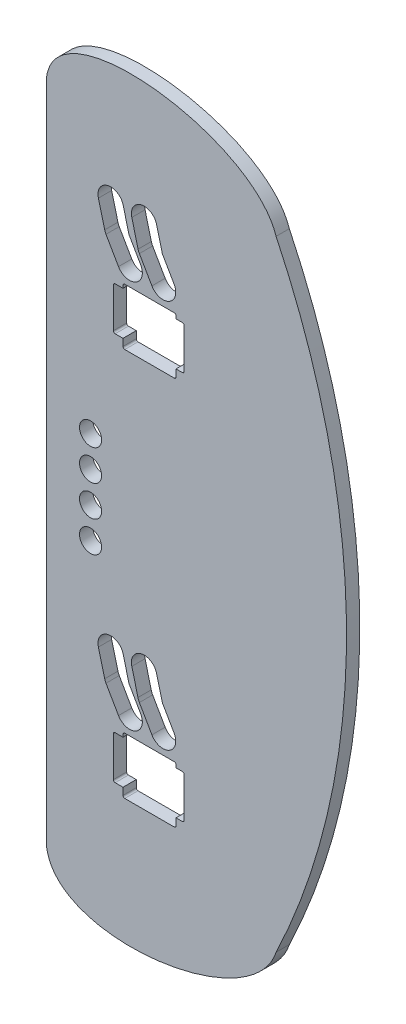
SolidWorks part; units mm, degrees
material "Pine"
ref_plane "Front Plane" through (0, 0, 0) normal (0, 0, 1) x (1, 0, 0)
ref_plane "Top Plane" through (0, 0, 0) normal (0, 1, 0) x (1, 0, 0)
ref_plane "Right Plane" through (0, 0, 0) normal (1, 0, 0) x (0, 0, -1)
sketch "Sketch1" plane through (0, 0, 0) normal (0, 1, 0) x (1, 0, 0)
  line L0 (-92.9216, 89.0184) -> (669.0784, 89.0184)
  line L1 (669.0784, 89.0184) -> (669.0784, 419.2184)
  line L2 (-92.9216, 89.0184) -> (-92.9216, 419.2184)
  line L5 (110.2784, 495.4184) -> (465.8784, 495.4184)
  line L8 (110.2784, 495.4184) -> (-92.9216, 419.2184)
  line L9 (465.8784, 495.4184) -> (669.0784, 419.2184)
  line L10 (-92.9216, 495.4184) -> (669.0784, 495.4184) construction
sketch "Sketch2" plane through (0, 0, 0) normal (0, 0, 1) x (1, 0, 0)
  line L95 (1361.0966, 1819.7347) -> (1361.0966, 996.3635)
  arc A0 (1691.2966, 1027.0491) -> (1691.2966, 1789.0491) centre (733.0004, 1408.0491) ccw
  spline S0 degree 3 poles (1691.2966, 1027.0491) (1656.7077, 922.0591) (1371.3251, 886.2968) (1361.0966, 996.3635) knots 0 0 0 0 7.629784 7.629784 7.629784 7.629784
  spline S1 degree 3 poles (1691.2966, 1789.0491) (1656.7629, 1894.0573) (1371.3251, 1929.8013) (1361.0966, 1819.7347) knots 0 0 0 0 7.638295 7.638295 7.638295 7.638295
sketch "Sketch5" plane through (0, 0, 0) normal (0, 0, 1) x (1, 0, 0)
  line L0 (1361.0966, 1819.7347) -> (1361.0966, 996.3635)
  line L1 (1361.0966, 1789.0491) -> (1361.0966, 1027.0491)
  line L2 (1540.0357, 1006.8697) -> (1540.0357, 1016.3947)
  line L3 (1486.0607, 1097.3572) -> (1486.0607, 1006.8697) construction
  line L4 (1486.0607, 1102.1197) -> (1486.0607, 1092.5947)
  line L5 (1540.0357, 1006.8697) -> (1540.0357, 1097.3572) construction
  line L6 (1544.7982, 1102.1197) -> (1481.2982, 1102.1197) construction
  line L7 (1486.0607, 1006.8697) -> (1540.0357, 1006.8697)
  line L8 (1479.7107, 1016.3947) -> (1546.3857, 1016.3947)
  line L9 (1546.3857, 1016.3947) -> (1546.3857, 1092.5947)
  line L10 (1546.3857, 1092.5947) -> (1479.7107, 1092.5947)
  line L11 (1479.7107, 1016.3947) -> (1479.7107, 1092.5947)
  line L12 (1540.0357, 1548.8399) -> (1540.0357, 1558.3649)
  line L13 (1486.0607, 1548.8399) -> (1540.0357, 1548.8399)
  line L14 (1546.3857, 1634.5649) -> (1479.7107, 1634.5649)
  line L15 (1486.0607, 1644.0899) -> (1486.0607, 1634.5649)
  line L16 (1479.7107, 1558.3649) -> (1479.7107, 1634.5649)
  line L17 (1540.0357, 1644.0899) -> (1486.0607, 1644.0899)
  line L18 (1479.7107, 1558.3649) -> (1546.3857, 1558.3649)
  line L19 (1546.3857, 1558.3649) -> (1546.3857, 1634.5649)
  line L20 (1540.0357, 1092.5947) -> (1540.0357, 1102.1197)
  line L21 (1486.0607, 1016.3947) -> (1486.0607, 1006.8697)
  line L22 (1540.0357, 1634.5649) -> (1540.0357, 1644.0899)
  line L23 (1486.0607, 1558.3649) -> (1486.0607, 1548.8399)
  line L95 (1361.0966, 1819.7347) -> (1361.0966, 996.3635)
  line L115 (1540.0357, 1102.1197) -> (1486.0607, 1102.1197)
  line L199 (1363.2449, 1823.8418) -> (1361.0966, 1819.7347)
  line L200 (1361.0966, 1819.7347) -> (1361.7967, 1824.3165)
  line L201 (1361.7967, 1824.3165) -> (1363.2449, 1823.8418)
  line L202 (1540.0357, 1097.3572) -> (1486.0607, 1097.3572) construction
  line L203 (1481.2982, 1102.1197) -> (1481.2982, 1006.8697) construction
  line L204 (1544.7982, 1006.8697) -> (1544.7982, 1102.1197) construction
  arc A0 (1691.2966, 1027.0491) -> (1691.2966, 1789.0491) centre (733.0004, 1408.0491) ccw
  circle A1 centre (1506.0488, 1194.0197) radius 15.875
  circle A2 centre (1515.0488, 1159.0198) radius 15.875
  circle A3 centre (1533.0488, 1127.7698) radius 15.875
  circle A4 centre (1467.0488, 1159.0198) radius 15.875
  circle A5 centre (1485.0488, 1127.7698) radius 15.875
  circle A6 centre (1458.0488, 1194.0197) radius 15.875
  circle A7 centre (1513.0482, 1054.4947) radius 12
  circle A8 centre (1506.0488, 1735.9899) radius 15.875
  circle A9 centre (1515.0488, 1700.99) radius 15.875
  circle A10 centre (1533.0488, 1669.74) radius 15.875
  circle A11 centre (1467.0488, 1700.99) radius 15.875
  circle A12 centre (1485.0488, 1669.74) radius 15.875
  circle A13 centre (1458.0488, 1735.9899) radius 15.875
  circle A15 centre (1483.5084, 1375.1967) radius 12
  circle A16 centre (1483.9827, 1438.6917) radius 12
  circle A17 centre (1551.8392, 1408.0266) radius 29.9999
  circle A18 centre (1409.3368, 1408.0266) radius 15.9995
  circle A19 centre (1513.0482, 1596.4649) radius 12
  arc A30 (1539.4945, 1725.9331) -> (1482.0488, 1761.3623) centre (1506.0488, 1735.9899) ccw
  arc A32 (1549.9668, 1700.2938) -> (1539.4945, 1725.9331) centre (1515.0488, 1700.99) ccw
  arc A41 (1509.0488, 1644.3676) -> (1549.9668, 1700.2938) centre (1533.0488, 1669.74) ccw
  arc A46 (1450.1308, 1670.4362) -> (1509.0488, 1644.3676) centre (1485.0488, 1669.74) ccw
  arc A47 (1433.6031, 1711.0467) -> (1450.1308, 1670.4362) centre (1467.0488, 1700.99) ccw
  arc A50 (1482.0488, 1761.3623) -> (1433.6031, 1711.0467) centre (1458.0488, 1735.9899) ccw
  arc A64 (1509.0488, 1102.3974) -> (1549.9668, 1158.3235) centre (1533.0488, 1127.7698) ccw
  arc A66 (1450.1308, 1128.466) -> (1509.0488, 1102.3974) centre (1485.0488, 1127.7698) ccw
  arc A68 (1433.6031, 1169.0765) -> (1450.1308, 1128.466) centre (1467.0488, 1159.0198) ccw
  arc A70 (1539.4945, 1183.9629) -> (1482.0488, 1219.3921) centre (1506.0488, 1194.0197) ccw
  arc A72 (1549.9668, 1158.3235) -> (1539.4945, 1183.9629) centre (1515.0488, 1159.0198) ccw
  arc A73 (1482.0488, 1219.3921) -> (1433.6031, 1169.0765) centre (1458.0488, 1194.0197) ccw
  arc A86 (1474.249, 1382.8299) -> (1489.0021, 1364.5282) centre (1483.5084, 1375.1967) ccw
  arc A89 (1488.8753, 1449.649) -> (1474.6166, 1431.19) centre (1483.9827, 1438.6917) ccw
  arc A97 (1557.861, 1378.6372) -> (1557.0728, 1437.5665) centre (1551.8392, 1408.0266) ccw
  arc A99 (1420.1657, 1419.8299) -> (1400.5179, 1421.402) centre (1409.3362, 1408.0491) ccw
  arc A100 (1402.6554, 1393.5084) -> (1419.641, 1395.8067) centre (1409.3362, 1408.0491) ccw
  spline S0 degree 3 poles (1691.2966, 1027.0491) (1656.7077, 922.0591) (1371.3251, 886.2968) (1361.0966, 996.3635) knots 0 0 0 0 7.629784 7.629784 7.629784 7.629784
  spline S1 degree 3 poles (1691.2966, 1789.0491) (1656.7629, 1894.0573) (1371.3251, 1929.8013) (1361.0966, 1819.7347) knots 0 0 0 0 7.638295 7.638295 7.638295 7.638295
  dimension "D1" = 4.7625
sketch "Sketch8" plane through (0, 0, 0) normal (0, 0, 1) x (1, 0, 0)
  line L2 (1540.0357, 1006.8697) -> (1540.0357, 1016.3947)
  line L3 (1486.0607, 1097.3572) -> (1486.0607, 1006.8697) construction
  line L4 (1486.0607, 1102.1197) -> (1486.0607, 1092.5947)
  line L5 (1540.0357, 1006.8697) -> (1540.0357, 1097.3572) construction
  line L6 (1544.7982, 1102.1197) -> (1481.2982, 1102.1197) construction
  line L7 (1486.0607, 1006.8697) -> (1540.0357, 1006.8697)
  line L8 (1479.7107, 1016.3947) -> (1546.3857, 1016.3947)
  line L9 (1546.3857, 1016.3947) -> (1546.3857, 1092.5947)
  line L10 (1546.3857, 1092.5947) -> (1479.7107, 1092.5947)
  line L11 (1479.7107, 1016.3947) -> (1479.7107, 1092.5947)
  line L12 (1540.0357, 1548.8399) -> (1540.0357, 1558.3649)
  line L13 (1486.0607, 1548.8399) -> (1540.0357, 1548.8399)
  line L14 (1546.3857, 1634.5649) -> (1479.7107, 1634.5649)
  line L15 (1486.0607, 1644.0899) -> (1486.0607, 1634.5649)
  line L16 (1479.7107, 1558.3649) -> (1479.7107, 1634.5649)
  line L17 (1540.0357, 1644.0899) -> (1486.0607, 1644.0899)
  line L18 (1479.7107, 1558.3649) -> (1546.3857, 1558.3649)
  line L19 (1546.3857, 1558.3649) -> (1546.3857, 1634.5649)
  line L20 (1540.0357, 1092.5947) -> (1540.0357, 1102.1197)
  line L21 (1486.0607, 1016.3947) -> (1486.0607, 1006.8697)
  line L22 (1540.0357, 1634.5649) -> (1540.0357, 1644.0899)
  line L23 (1486.0607, 1558.3649) -> (1486.0607, 1548.8399)
  line L95 (1361.0966, 1819.7347) -> (1361.0966, 996.3635)
  line L115 (1540.0357, 1102.1197) -> (1486.0607, 1102.1197)
  line L202 (1540.0357, 1097.3572) -> (1486.0607, 1097.3572) construction
  line L203 (1481.2982, 1102.1197) -> (1481.2982, 1006.8697) construction
  line L204 (1544.7982, 1006.8697) -> (1544.7982, 1102.1197) construction
  arc A0 (1691.2966, 1027.0491) -> (1691.2966, 1789.0491) centre (733.0004, 1408.0491) ccw
  circle A1 centre (1506.0488, 1194.0197) radius 15.875
  circle A2 centre (1515.0488, 1159.0198) radius 15.875
  circle A3 centre (1533.0488, 1127.7698) radius 15.875
  circle A4 centre (1467.0488, 1159.0198) radius 15.875
  circle A5 centre (1485.0488, 1127.7698) radius 15.875
  circle A6 centre (1458.0488, 1194.0197) radius 15.875
  circle A7 centre (1513.0482, 1054.4947) radius 12
  circle A8 centre (1506.0488, 1735.9899) radius 15.875
  circle A9 centre (1515.0488, 1700.99) radius 15.875
  circle A10 centre (1533.0488, 1669.74) radius 15.875
  circle A11 centre (1467.0488, 1700.99) radius 15.875
  circle A12 centre (1485.0488, 1669.74) radius 15.875
  circle A13 centre (1458.0488, 1735.9899) radius 15.875
  circle A15 centre (1483.5084, 1375.1967) radius 12
  circle A16 centre (1483.9827, 1438.6917) radius 12
  circle A17 centre (1551.8392, 1408.0266) radius 29.9999
  circle A18 centre (1409.3368, 1408.0266) radius 15.9995
  circle A19 centre (1513.0482, 1596.4649) radius 12
  arc A30 (1539.4945, 1725.9331) -> (1482.0488, 1761.3623) centre (1506.0488, 1735.9899) ccw
  arc A32 (1549.9668, 1700.2938) -> (1539.4945, 1725.9331) centre (1515.0488, 1700.99) ccw
  arc A41 (1509.0488, 1644.3676) -> (1549.9668, 1700.2938) centre (1533.0488, 1669.74) ccw
  arc A46 (1450.1308, 1670.4362) -> (1509.0488, 1644.3676) centre (1485.0488, 1669.74) ccw
  arc A47 (1433.6031, 1711.0467) -> (1450.1308, 1670.4362) centre (1467.0488, 1700.99) ccw
  arc A50 (1482.0488, 1761.3623) -> (1433.6031, 1711.0467) centre (1458.0488, 1735.9899) ccw
  arc A64 (1509.0488, 1102.3974) -> (1549.9668, 1158.3235) centre (1533.0488, 1127.7698) ccw
  arc A66 (1450.1308, 1128.466) -> (1509.0488, 1102.3974) centre (1485.0488, 1127.7698) ccw
  arc A68 (1433.6031, 1169.0765) -> (1450.1308, 1128.466) centre (1467.0488, 1159.0198) ccw
  arc A70 (1539.4945, 1183.9629) -> (1482.0488, 1219.3921) centre (1506.0488, 1194.0197) ccw
  arc A72 (1549.9668, 1158.3235) -> (1539.4945, 1183.9629) centre (1515.0488, 1159.0198) ccw
  arc A73 (1482.0488, 1219.3921) -> (1433.6031, 1169.0765) centre (1458.0488, 1194.0197) ccw
  arc A86 (1474.249, 1382.8299) -> (1489.0021, 1364.5282) centre (1483.5084, 1375.1967) ccw
  arc A89 (1488.8753, 1449.649) -> (1474.6166, 1431.19) centre (1483.9827, 1438.6917) ccw
  arc A97 (1557.861, 1378.6372) -> (1557.0728, 1437.5665) centre (1551.8392, 1408.0266) ccw
  arc A99 (1420.1657, 1419.8299) -> (1400.5179, 1421.402) centre (1409.3362, 1408.0491) ccw
  arc A100 (1402.6554, 1393.5084) -> (1419.641, 1395.8067) centre (1409.3362, 1408.0491) ccw
  spline S0 degree 3 poles (1691.2966, 1027.0491) (1656.7077, 922.0591) (1371.3251, 886.2968) (1361.0966, 996.3635) knots 0 0 0 0 7.629784 7.629784 7.629784 7.629784
  spline S1 degree 3 poles (1691.2966, 1789.0491) (1656.7629, 1894.0573) (1371.3251, 1929.8013) (1361.0966, 1819.7347) knots 0 0 0 0 7.638295 7.638295 7.638295 7.638295
  dimension "D1" = 4.7625
sketch "Sketch9" plane through (0, 0, 0) normal (0, 0, 1) x (1, 0, 0)
  line L0 (1361.0966, 1884.2991) -> (1361.0966, 1060.9279)
  line L1 (1361.0966, 1472.6135) -> (1839.973, 1472.6135)
  circle A20 centre (1506.0488, 1272.2885) radius 12
  circle A21 centre (1515.0488, 1237.2885) radius 12
  circle A22 centre (1533.0488, 1206.0385) radius 12
  circle A23 centre (1467.0488, 1237.2885) radius 12
  circle A24 centre (1485.0488, 1206.0385) radius 12
  circle A25 centre (1458.0488, 1272.2885) radius 12
  circle A26 centre (1513.0482, 1142.2885) radius 12
  circle A27 centre (1501.6642, 1830.4221) radius 12
  circle A28 centre (1510.6642, 1795.4221) radius 12
  circle A29 centre (1528.6642, 1764.1721) radius 12
  circle A31 centre (1462.6642, 1795.4221) radius 12
  circle A33 centre (1480.6642, 1764.1721) radius 12
  circle A34 centre (1453.6642, 1830.4221) radius 12
  circle A35 centre (1508.6636, 1700.4221) radius 12
sketch "Sketch13" plane through (0, 0, 0) normal (0, 0, 1) x (1, 0, 0)
  line L0 (1439.599, 1277.0692) -> (1448.5991, 1242.0693)
  line L1 (1450.5414, 1237.3053) -> (1468.5414, 1206.0553)
  line L2 (1540.0357, 1097.2035) -> (1540.0357, 1104.1885)
  line L3 (1486.0607, 1185.151) -> (1486.0607, 1006.8697) construction
  line L4 (1486.0607, 1187.3735) -> (1486.0607, 1180.3885)
  line L5 (1540.0357, 1006.8697) -> (1540.0357, 1185.151) construction
  line L6 (1544.7982, 1189.9135) -> (1481.2982, 1189.9135) construction
  line L7 (1488.6007, 1094.6635) -> (1537.4957, 1094.6635)
  line L8 (1482.2507, 1104.1885) -> (1543.8457, 1104.1885)
  line L9 (1546.3857, 1106.7285) -> (1546.3857, 1177.8485)
  line L10 (1543.8457, 1180.3885) -> (1482.2507, 1180.3885)
  line L11 (1479.7107, 1106.7285) -> (1479.7107, 1177.8485)
  line L12 (1540.0357, 1656.0035) -> (1540.0357, 1662.9885)
  line L13 (1488.6007, 1653.4635) -> (1537.4957, 1653.4635)
  line L14 (1543.8457, 1739.1885) -> (1482.2507, 1739.1885)
  line L15 (1486.0607, 1746.1735) -> (1486.0607, 1739.1885)
  line L16 (1479.7107, 1665.5285) -> (1479.7107, 1736.6485)
  line L17 (1537.4957, 1748.7135) -> (1488.6007, 1748.7135)
  line L18 (1482.2507, 1662.9885) -> (1543.8457, 1662.9885)
  line L19 (1546.3857, 1665.5285) -> (1546.3857, 1736.6485)
  line L20 (1540.0357, 1180.3885) -> (1540.0357, 1187.3735)
  line L21 (1486.0607, 1104.1885) -> (1486.0607, 1097.2035)
  line L22 (1540.0357, 1739.1885) -> (1540.0357, 1746.1735)
  line L23 (1486.0607, 1662.9885) -> (1486.0607, 1656.0035)
  line L24 (1485.0488, 1196.5135) -> (1533.0488, 1196.5135)
  line L25 (1550.8991, 1222.2168) -> (1533.383, 1252.007)
  line L26 (1524.4986, 1286.5577) -> (1533.383, 1252.007)
  line L27 (1459.748, 1300.7875) -> (1504.3496, 1300.7875)
  line L28 (1439.599, 1835.8692) -> (1448.5991, 1800.8693)
  line L29 (1450.5414, 1796.1053) -> (1468.5414, 1764.8553)
  line L30 (1485.0488, 1755.3135) -> (1533.0488, 1755.3135)
  line L31 (1549.5562, 1783.8718) -> (1532.852, 1812.8721)
  line L32 (1524.4986, 1845.3577) -> (1532.852, 1812.8721)
  line L33 (1458.0488, 1859.6635) -> (1506.0488, 1859.6635)
  line L34 (1513.0482, 1748.7135) -> (1513.0482, 1755.3135)
  line L38 (1513.0482, 1189.9135) -> (1513.0482, 1196.5135)
  line L95 (1361.0966, 1948.8635) -> (1361.0966, 996.3635)
  line L115 (1537.4957, 1189.9135) -> (1488.6007, 1189.9135)
  line L202 (1540.0357, 1185.151) -> (1486.0607, 1185.151) construction
  line L203 (1481.2982, 1189.9135) -> (1481.2982, 1006.8697) construction
  line L204 (1544.7982, 1006.8697) -> (1544.7982, 1189.9135) construction
  arc A0 (1691.2966, 1027.0491) -> (1691.2966, 1918.1779) centre (761.2616, 1472.6135) ccw
  arc A1 (1524.4986, 1286.5577) -> (1504.3496, 1300.7875) centre (1506.0488, 1281.8135) ccw
  arc A2 (1479.7107, 1177.8485) -> (1482.2507, 1180.3885) centre (1482.2507, 1177.8485) cw
  arc A3 (1533.0488, 1196.5135) -> (1547.5414, 1227.9274) centre (1533.0488, 1215.5635) ccw
  arc A4 (1448.5991, 1242.0693) -> (1450.5414, 1237.3053) centre (1467.0488, 1246.8135) ccw
  arc A5 (1468.5414, 1206.0553) -> (1485.0488, 1196.5135) centre (1485.0488, 1215.5635) ccw
  arc A6 (1459.748, 1300.7875) -> (1439.599, 1277.0692) centre (1458.0488, 1281.8135) ccw
  circle A7 centre (1513.0482, 1142.2885) radius 12
  arc A8 (1524.4986, 1845.3577) -> (1506.0488, 1859.6635) centre (1506.0488, 1840.6135) ccw
  arc A9 (1546.3857, 1177.8485) -> (1543.8457, 1180.3885) centre (1543.8457, 1177.8485) ccw
  arc A10 (1533.0488, 1755.3135) -> (1549.5562, 1783.8718) centre (1533.0488, 1774.3635) ccw
  arc A11 (1448.5991, 1800.8693) -> (1450.5414, 1796.1053) centre (1467.0488, 1805.6135) ccw
  arc A12 (1543.8457, 1104.1885) -> (1546.3857, 1106.7285) centre (1543.8457, 1106.7285) ccw
  arc A13 (1458.0488, 1859.6635) -> (1439.599, 1835.8692) centre (1458.0488, 1840.6135) ccw
  arc A14 (1482.2507, 1104.1885) -> (1479.7107, 1106.7285) centre (1482.2507, 1106.7285) cw
  arc A15 (1488.6007, 1094.6635) -> (1486.0607, 1097.2035) centre (1488.6007, 1097.2035) cw
  arc A16 (1537.4957, 1094.6635) -> (1540.0357, 1097.2035) centre (1537.4957, 1097.2035) ccw
  arc A17 (1479.7107, 1736.6485) -> (1482.2507, 1739.1885) centre (1482.2507, 1736.6485) cw
  arc A18 (1546.3857, 1736.6485) -> (1543.8457, 1739.1885) centre (1543.8457, 1736.6485) ccw
  circle A19 centre (1513.0482, 1701.0885) radius 12
  arc A20 (1468.5414, 1764.8553) -> (1485.0488, 1755.3135) centre (1485.0488, 1774.3635) ccw
  arc A21 (1540.0357, 1746.1735) -> (1537.4957, 1748.7135) centre (1537.4957, 1746.1735) ccw
  arc A22 (1486.0607, 1746.1735) -> (1488.6007, 1748.7135) centre (1488.6007, 1746.1735) cw
  arc A23 (1543.8457, 1662.9885) -> (1546.3857, 1665.5285) centre (1543.8457, 1665.5285) ccw
  arc A24 (1537.4957, 1653.4635) -> (1540.0357, 1656.0035) centre (1537.4957, 1656.0035) ccw
  arc A25 (1488.6007, 1653.4635) -> (1486.0607, 1656.0035) centre (1488.6007, 1656.0035) cw
  arc A26 (1479.7107, 1665.5285) -> (1482.2507, 1662.9885) centre (1482.2507, 1665.5285) ccw
  arc A27 (1540.0357, 1187.3735) -> (1537.4957, 1189.9135) centre (1537.4957, 1187.3735) ccw
  arc A28 (1486.0607, 1187.3735) -> (1488.6007, 1189.9135) centre (1488.6007, 1187.3735) cw
  circle A29 centre (1424.5966, 1539.2885) radius 15.875
  circle A30 centre (1424.5966, 1494.8385) radius 15.875
  circle A31 centre (1424.5966, 1450.3885) radius 15.875
  circle A32 centre (1424.5966, 1405.9385) radius 15.875
  spline S0 degree 3 poles (1691.2966, 1027.0491) (1656.7077, 922.0591) (1371.3251, 886.2968) (1361.0966, 996.3635) knots 0 0 0 0 7.629784 7.629784 7.629784 7.629784
  spline S1 degree 3 poles (1691.2966, 1918.1779) (1656.7629, 2023.1861) (1371.3251, 2058.9302) (1361.0966, 1948.8635) knots 0 0 0 0 7.638295 7.638295 7.638295 7.638295
  dimension "D2" = 2.54
  dimension "D4" = 2.54
  dimension "D5" = 2.54
  dimension "D6" = 2.54
  dimension "D7" = 2.54
  dimension "D8" = 2.54
  dimension "D9" = 2.54
  dimension "D3" = 2.54
  dimension "D15" = 2.54
  dimension "D1" = 4.7625
sketch "Sketch17" plane through (0, 0, 0) normal (0, 0, 1) x (1, 0, 0)
  line L2 (1509.3308, 1749.8224) -> (1509.3308, 1754.2046)
  line L4 (1523.1267, 1289.3333) -> (1531.2884, 1257.5934)
  line L5 (1459.9849, 1122.4424) -> (1556.5049, 1122.4424)
  line L6 (1531.5474, 1256.9582) -> (1547.8672, 1228.6251)
  line L7 (1547.4308, 1184.6724) -> (1556.5049, 1184.6724)
  line L8 (1432.2032, 1278.2957) -> (1441.2032, 1243.2958)
  line L9 (1547.4308, 1112.2824) -> (1547.4308, 1188.4824)
  line L10 (1459.9849, 1184.6724) -> (1471.2308, 1184.6724)
  line L11 (1473.7708, 1191.0224) -> (1544.8908, 1191.0224)
  line L14 (1547.4308, 1671.0824) -> (1547.4308, 1747.2824)
  line L15 (1471.2308, 1188.4824) -> (1471.2308, 1112.2824)
  line L16 (1473.7708, 1749.8224) -> (1544.8908, 1749.8224)
  line L17 (1432.2032, 1837.0957) -> (1441.2032, 1802.0958)
  line L18 (1471.2308, 1747.2824) -> (1471.2308, 1671.0824)
  line L19 (1461.4626, 1765.304) -> (1443.4626, 1796.554)
  line L20 (1461.4626, 1206.504) -> (1443.4626, 1237.754)
  line L21 (1547.4308, 1122.4424) -> (1556.5049, 1122.4424)
  line L22 (1547.4308, 1681.2424) -> (1556.5049, 1681.2424)
  line L23 (1523.1267, 1848.1333) -> (1531.2884, 1816.3934)
  line L24 (1453.665, 1305.9745) -> (1501.6649, 1305.9745)
  line L26 (1473.7708, 1109.7424) -> (1544.8908, 1109.7424)
  line L27 (1480.665, 1754.2046) -> (1528.6649, 1754.2046)
  line L28 (1531.5474, 1815.7582) -> (1547.8672, 1787.4251)
  line L29 (1453.665, 1864.7745) -> (1501.6649, 1864.7745)
  line L30 (1480.665, 1195.4046) -> (1528.6649, 1195.4046)
  line L31 (1559.0449, 1182.1324) -> (1559.0449, 1124.9824)
  line L32 (1457.4449, 1182.1324) -> (1457.4449, 1124.9824)
  line L34 (1457.4449, 1740.9324) -> (1457.4449, 1683.7824)
  line L35 (1473.7708, 1668.5424) -> (1544.8908, 1668.5424)
  line L36 (1459.9849, 1743.4724) -> (1471.2308, 1743.4724)
  line L37 (1559.0449, 1740.9324) -> (1559.0449, 1683.7824)
  line L39 (1459.9849, 1681.2424) -> (1556.5049, 1681.2424)
  line L41 (1547.4308, 1743.4724) -> (1556.5049, 1743.4724)
  line L95 (1361.0966, 1948.8635) -> (1361.0966, 996.3635)
  arc A0 (1691.2966, 1027.0491) -> (1691.2966, 1918.1779) centre (761.2616, 1472.6135) ccw
  arc A1 (1441.2032, 1802.0958) -> (1443.4626, 1796.554) centre (1462.665, 1807.6146) ccw
  arc A2 (1523.1267, 1289.3333) -> (1501.6649, 1305.9745) centre (1501.6649, 1283.8145) ccw
  circle A3 centre (1510.6649, 1248.8146) radius 12
  arc A4 (1471.2308, 1188.4824) -> (1473.7708, 1191.0224) centre (1473.7708, 1188.4824) cw
  arc A5 (1531.5474, 1256.9582) -> (1531.2884, 1257.5934) centre (1533.7484, 1258.226) cw
  arc A6 (1461.4626, 1765.304) -> (1480.665, 1754.2046) centre (1480.665, 1776.3646) ccw
  circle A7 centre (1462.665, 1248.8146) radius 12
  arc A8 (1453.665, 1864.7745) -> (1432.2032, 1837.0957) centre (1453.665, 1842.6145) ccw
  circle A9 centre (1508.6644, 1153.8145) radius 12
  arc A10 (1523.1267, 1848.1333) -> (1501.6649, 1864.7745) centre (1501.6649, 1842.6145) ccw
  arc A11 (1531.5474, 1815.7582) -> (1531.2884, 1816.3934) centre (1533.7484, 1817.026) cw
  arc A12 (1441.2032, 1243.2958) -> (1443.4626, 1237.754) centre (1462.665, 1248.8146) ccw
  arc A13 (1528.6649, 1754.2046) -> (1547.8672, 1787.4251) centre (1528.6649, 1776.3646) ccw
  arc A14 (1528.6649, 1195.4046) -> (1547.8672, 1228.6251) centre (1528.6649, 1217.5646) ccw
  arc A15 (1544.8908, 1191.0224) -> (1547.4308, 1188.4824) centre (1544.8908, 1188.4824) cw
  arc A16 (1453.665, 1305.9745) -> (1432.2032, 1278.2957) centre (1453.665, 1283.8145) ccw
  arc A17 (1471.2308, 1747.2824) -> (1473.7708, 1749.8224) centre (1473.7708, 1747.2824) cw
  arc A18 (1473.7708, 1668.5424) -> (1471.2308, 1671.0824) centre (1473.7708, 1671.0824) cw
  circle A19 centre (1508.6644, 1712.6145) radius 12
  circle A20 centre (1453.665, 1283.8145) radius 12
  circle A21 centre (1528.6649, 1217.5646) radius 12
  arc A22 (1556.5049, 1122.4424) -> (1559.0449, 1124.9824) centre (1556.5049, 1124.9824) ccw
  arc A23 (1544.8908, 1668.5424) -> (1547.4308, 1671.0824) centre (1544.8908, 1671.0824) ccw
  circle A24 centre (1480.665, 1217.5646) radius 12
  arc A25 (1556.5049, 1184.6724) -> (1559.0449, 1182.1324) centre (1556.5049, 1182.1324) cw
  arc A26 (1544.8908, 1749.8224) -> (1547.4308, 1747.2824) centre (1544.8908, 1747.2824) cw
  arc A27 (1473.7708, 1109.7424) -> (1471.2308, 1112.2824) centre (1473.7708, 1112.2824) cw
  circle A28 centre (1501.6649, 1283.8145) radius 12
  circle A29 centre (1424.5966, 1539.2885) radius 15.875
  circle A30 centre (1424.5966, 1494.8385) radius 15.875
  circle A31 centre (1424.5966, 1450.3885) radius 15.875
  circle A32 centre (1424.5966, 1405.9385) radius 15.875
  arc A33 (1459.9849, 1743.4724) -> (1457.4449, 1740.9324) centre (1459.9849, 1740.9324) ccw
  arc A34 (1457.4449, 1683.7824) -> (1459.9849, 1681.2424) centre (1459.9849, 1683.7824) ccw
  arc A35 (1556.5049, 1681.2424) -> (1559.0449, 1683.7824) centre (1556.5049, 1683.7824) ccw
  arc A36 (1556.5049, 1743.4724) -> (1559.0449, 1740.9324) centre (1556.5049, 1740.9324) cw
  arc A37 (1459.9849, 1184.6724) -> (1457.4449, 1182.1324) centre (1459.9849, 1182.1324) ccw
  arc A38 (1461.4626, 1206.504) -> (1480.665, 1195.4046) centre (1480.665, 1217.5646) ccw
  arc A39 (1544.8908, 1109.7424) -> (1547.4308, 1112.2824) centre (1544.8908, 1112.2824) ccw
  circle A40 centre (1501.6649, 1842.6145) radius 12
  circle A41 centre (1510.6649, 1807.6146) radius 12
  circle A42 centre (1528.6649, 1776.3646) radius 12
  circle A43 centre (1462.665, 1807.6146) radius 12
  circle A44 centre (1480.665, 1776.3646) radius 12
  circle A45 centre (1453.665, 1842.6145) radius 12
  circle A46 centre (1508.6644, 1712.6145) radius 12
  arc A47 (1457.4449, 1124.9824) -> (1459.9849, 1122.4424) centre (1459.9849, 1124.9824) ccw
  spline S0 degree 3 poles (1691.2966, 1027.0491) (1656.7077, 922.0591) (1371.3251, 886.2968) (1361.0966, 996.3635) knots 0 0 0 0 7.629784 7.629784 7.629784 7.629784
  spline S1 degree 3 poles (1691.2966, 1918.1779) (1656.7629, 2023.1861) (1371.3251, 2058.9302) (1361.0966, 1948.8635) knots 0 0 0 0 7.638295 7.638295 7.638295 7.638295
  dimension "D3" = 2.54
  dimension "D10" = 2.54
sketch "Sketch19" plane through (0, 0, 0) normal (0, 0, 1) x (1, 0, 0)
  line L0 (1435.8931, 1279.2446) -> (1444.8931, 1244.2446)
  line L1 (1446.7641, 1239.6556) -> (1464.7641, 1208.4056)
  line L2 (1435.8931, 1838.0446) -> (1444.8931, 1803.0447)
  line L3 (1446.7641, 1798.4557) -> (1464.7641, 1767.2057)
  line L4 (1544.5658, 1226.7235) -> (1527.9867, 1255.5065)
  line L5 (1459.9849, 1122.4424) -> (1556.5049, 1122.4424)
  line L6 (1519.4367, 1288.3844) -> (1527.7277, 1256.1417)
  line L7 (1547.4308, 1184.6724) -> (1556.5049, 1184.6724)
  line L8 (1483.8946, 1279.2387) -> (1493.0723, 1243.5972)
  line L9 (1547.4308, 1112.2824) -> (1547.4308, 1188.4824)
  line L10 (1459.9849, 1184.6724) -> (1471.2308, 1184.6724)
  line L11 (1473.7708, 1191.0224) -> (1544.8908, 1191.0224)
  line L12 (1494.764, 1239.6557) -> (1512.764, 1208.4057)
  line L13 (1471.4367, 1288.3844) -> (1479.7345, 1256.1153)
  line L14 (1547.4308, 1671.0824) -> (1547.4308, 1747.2824)
  line L15 (1471.2308, 1188.4824) -> (1471.2308, 1112.2824)
  line L16 (1473.7708, 1749.8224) -> (1544.8908, 1749.8224)
  line L17 (1479.9868, 1814.3065) -> (1496.5658, 1785.5234)
  line L18 (1471.2308, 1747.2824) -> (1471.2308, 1671.0824)
  line L19 (1471.4368, 1847.1844) -> (1479.7278, 1814.9417)
  line L20 (1497.4224, 1225.0419) -> (1479.9903, 1255.4858)
  line L21 (1547.4308, 1122.4424) -> (1556.5049, 1122.4424)
  line L22 (1547.4308, 1681.2424) -> (1556.5049, 1681.2424)
  line L23 (1483.8931, 1838.0446) -> (1492.8931, 1803.0447)
  line L24 (1494.764, 1798.4557) -> (1512.764, 1767.2057)
  line L25 (1527.9867, 1814.3065) -> (1544.5658, 1785.5235)
  line L26 (1473.7708, 1109.7424) -> (1544.8908, 1109.7424)
  line L27 (1527.7277, 1814.9417) -> (1519.4367, 1847.1844)
  line L31 (1559.0449, 1182.1324) -> (1559.0449, 1124.9824)
  line L32 (1457.4449, 1182.1324) -> (1457.4449, 1124.9824)
  line L34 (1457.4449, 1740.9324) -> (1457.4449, 1683.7824)
  line L35 (1473.7708, 1668.5424) -> (1544.8908, 1668.5424)
  line L36 (1459.9849, 1743.4724) -> (1471.2308, 1743.4724)
  line L37 (1559.0449, 1740.9324) -> (1559.0449, 1683.7824)
  line L39 (1459.9849, 1681.2424) -> (1556.5049, 1681.2424)
  line L41 (1547.4308, 1743.4724) -> (1556.5049, 1743.4724)
  line L95 (1361.0966, 1948.8635) -> (1361.0966, 996.3635)
  arc A0 (1691.2966, 1027.0491) -> (1691.2966, 1918.1779) centre (761.2616, 1472.6135) ccw
  arc A1 (1471.4368, 1847.1844) -> (1435.8931, 1838.0446) centre (1453.665, 1842.6145) ccw
  arc A2 (1471.4367, 1288.3844) -> (1435.8931, 1279.2446) centre (1453.6649, 1283.8145) ccw
  circle A3 centre (1510.6649, 1248.8146) radius 12
  arc A4 (1471.2308, 1188.4824) -> (1473.7708, 1191.0224) centre (1473.7708, 1188.4824) cw
  arc A5 (1444.8931, 1244.2446) -> (1446.7641, 1239.6556) centre (1462.6649, 1248.8145) ccw
  arc A6 (1479.9868, 1814.3065) -> (1479.7278, 1814.9417) centre (1482.1878, 1815.5743) cw
  circle A7 centre (1462.6649, 1248.8145) radius 12
  arc A8 (1464.7641, 1767.2057) -> (1496.5658, 1785.5234) centre (1480.6649, 1776.3646) ccw
  circle A9 centre (1508.6644, 1153.8145) radius 12
  arc A10 (1492.8931, 1803.0447) -> (1494.764, 1798.4557) centre (1510.6649, 1807.6146) ccw
  arc A12 (1464.7641, 1208.4056) -> (1495.5958, 1228.2319) centre (1480.665, 1217.5646) ccw
  arc A13 (1519.4367, 1847.1844) -> (1483.8931, 1838.0446) centre (1501.6649, 1842.6145) ccw
  arc A14 (1512.764, 1208.4057) -> (1544.5658, 1226.7235) centre (1528.6649, 1217.5646) ccw
  arc A15 (1544.8908, 1191.0224) -> (1547.4308, 1188.4824) centre (1544.8908, 1188.4824) cw
  arc A16 (1527.9867, 1255.5065) -> (1527.7277, 1256.1417) centre (1530.1877, 1256.7743) cw
  arc A17 (1471.2308, 1747.2824) -> (1473.7708, 1749.8224) centre (1473.7708, 1747.2824) cw
  arc A18 (1473.7708, 1668.5424) -> (1471.2308, 1671.0824) centre (1473.7708, 1671.0824) cw
  circle A19 centre (1508.6644, 1712.6145) radius 12
  circle A20 centre (1453.6649, 1283.8145) radius 12
  circle A21 centre (1528.6649, 1217.5646) radius 12
  arc A22 (1556.5049, 1122.4424) -> (1559.0449, 1124.9824) centre (1556.5049, 1124.9824) ccw
  arc A23 (1544.8908, 1668.5424) -> (1547.4308, 1671.0824) centre (1544.8908, 1671.0824) ccw
  circle A24 centre (1480.665, 1217.5646) radius 12
  arc A25 (1556.5049, 1184.6724) -> (1559.0449, 1182.1324) centre (1556.5049, 1182.1324) cw
  arc A26 (1544.8908, 1749.8224) -> (1547.4308, 1747.2824) centre (1544.8908, 1747.2824) cw
  arc A27 (1473.7708, 1109.7424) -> (1471.2308, 1112.2824) centre (1473.7708, 1112.2824) cw
  circle A28 centre (1501.6649, 1283.8145) radius 12
  circle A29 centre (1424.5966, 1539.2885) radius 15.875
  circle A30 centre (1424.5966, 1494.8385) radius 15.875
  circle A31 centre (1424.5966, 1450.3885) radius 15.875
  circle A32 centre (1424.5966, 1405.9385) radius 15.875
  arc A33 (1459.9849, 1743.4724) -> (1457.4449, 1740.9324) centre (1459.9849, 1740.9324) ccw
  arc A34 (1457.4449, 1683.7824) -> (1459.9849, 1681.2424) centre (1459.9849, 1683.7824) ccw
  arc A35 (1556.5049, 1681.2424) -> (1559.0449, 1683.7824) centre (1556.5049, 1683.7824) ccw
  arc A36 (1556.5049, 1743.4724) -> (1559.0449, 1740.9324) centre (1556.5049, 1740.9324) cw
  arc A37 (1459.9849, 1184.6724) -> (1457.4449, 1182.1324) centre (1459.9849, 1182.1324) ccw
  arc A38 (1519.4367, 1288.3844) -> (1483.8946, 1279.2387) centre (1501.6649, 1283.8145) ccw
  arc A39 (1544.8908, 1109.7424) -> (1547.4308, 1112.2824) centre (1544.8908, 1112.2824) ccw
  circle A40 centre (1501.6649, 1842.6145) radius 12
  circle A41 centre (1510.6649, 1807.6146) radius 12
  circle A42 centre (1528.6649, 1776.3646) radius 12
  circle A43 centre (1462.665, 1807.6146) radius 12
  circle A44 centre (1480.6649, 1776.3646) radius 12
  circle A45 centre (1453.665, 1842.6145) radius 12
  circle A46 centre (1508.6644, 1712.6145) radius 12
  arc A47 (1457.4449, 1124.9824) -> (1459.9849, 1122.4424) centre (1459.9849, 1124.9824) ccw
  circle A48 centre (1462.6649, 1248.8145) radius 18.35 construction
  circle A49 centre (1453.6649, 1283.8145) radius 18.35 construction
  circle A50 centre (1480.665, 1217.5646) radius 18.35 construction
  arc A51 (1479.9903, 1255.4858) -> (1479.7345, 1256.1153) centre (1482.1945, 1256.7479) cw
  circle A52 centre (1528.6649, 1217.5646) radius 18.35 construction
  arc A53 (1512.764, 1767.2057) -> (1544.5658, 1785.5235) centre (1528.6649, 1776.3646) ccw
  circle A54 centre (1501.6649, 1842.6145) radius 18.35 construction
  circle A55 centre (1501.6649, 1283.8145) radius 18.35 construction
  circle A56 centre (1510.6649, 1807.6146) radius 18.35 construction
  arc A57 (1492.7403, 1244.8863) -> (1494.764, 1239.6557) centre (1510.6649, 1248.8146) ccw
  arc A58 (1527.9867, 1814.3065) -> (1527.7277, 1814.9417) centre (1530.1877, 1815.5743) cw
  circle A59 centre (1528.6649, 1776.3646) radius 18.35 construction
  circle A60 centre (1480.6649, 1776.3646) radius 18.35 construction
  arc A61 (1444.8931, 1803.0447) -> (1446.7641, 1798.4557) centre (1462.665, 1807.6146) ccw
  circle A62 centre (1453.665, 1842.6145) radius 18.35 construction
  spline S0 degree 3 poles (1691.2966, 1027.0491) (1656.7077, 922.0591) (1371.3251, 886.2968) (1361.0966, 996.3635) knots 0 0 0 0 7.629784 7.629784 7.629784 7.629784
  spline S1 degree 3 poles (1691.2966, 1918.1779) (1656.7629, 2023.1861) (1371.3251, 2058.9302) (1361.0966, 1948.8635) knots 0 0 0 0 7.638295 7.638295 7.638295 7.638295
  dimension "D3" = 2.54
  dimension "D10" = 2.54
extrude "Boss-Extrude2" add sketch "Sketch19" along normal blind 19.05 contours A0 S1 L95 S0 L41 A36 L37 A35 L22 L14 A23 L35 A18 L18 L39 A34 L34 A33 L36 A17 L16 A26 A29 A30 A31 A32 A47 L32 A37 L10 L15 A4 L11 A15 L9 L7 A25 L31 A22 L5 A39 L26
